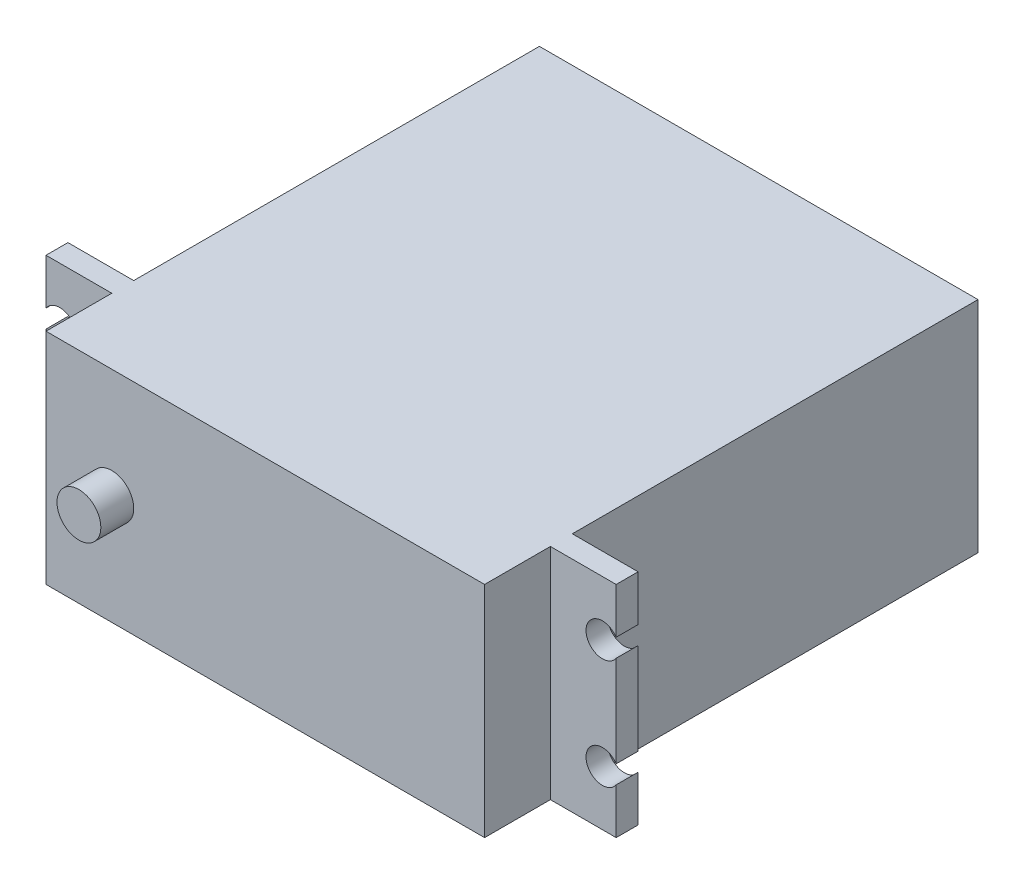
SolidWorks part; units mm, degrees
ref_plane "Plan de face" through (0, 0, 0) normal (0, 0, 1) x (1, 0, 0)
ref_plane "Plan de dessus" through (0, 0, 0) normal (0, 1, 0) x (1, 0, 0)
ref_plane "Plan de droite" through (0, 0, 0) normal (1, 0, 0) x (0, 0, -1)
sketch "Esquisse1" plane through (0, 0, 0) normal (0, 0, 1) x (1, 0, 0)
  line L1 (0, 0) -> (40, 0)
  line L2 (0, 0) -> (0, 20)
  line L3 (0, 20) -> (40, 20)
  line L4 (40, 0) -> (40, 20)
  dimension "D1" = 20
  dimension "D2" = 40
extrude "Boss.-Extru.1" add sketch "Esquisse1" along normal blind 45
sketch "Esquisse2" plane through (0, 0, 45) normal (0, 0, 1) x (1, 0, 0)
  line L0 (40, 20) -> (0, 20) construction
  line L1 (0, 20) -> (0, 0) construction
  circle A0 centre (6, 10) radius 2
  dimension "D1" = 4
  dimension "D2" = 10
  dimension "D3" = 6
extrude "Boss.-Extru.2" add sketch "Esquisse2" along normal blind 3
sketch "Esquisse3" plane through (0, 0, 0) normal (-1, 0, 0) x (0, 0, 1)
  line L0 (45, 20) -> (0, 20) construction
  line L1 (37, 20) -> (39, 20)
  line L2 (37, 20) -> (37, 0)
  line L3 (37, 0) -> (39, 0)
  line L4 (39, 20) -> (39, 0)
  line L5 (45, 0) -> (0, 0) construction
  line L6 (45, 20) -> (45, 0) construction
  dimension "D1" = 2
  dimension "D2" = 6
extrude "Boss.-Extru.3" add sketch "Esquisse3" along normal blind 6
sketch "Esquisse4" plane through (40, 0, 0) normal (1, 0, 0) x (0, 0, -1)
  line L0 (-45, 20) -> (0, 20) construction
  line L1 (-39, 20) -> (-37, 20)
  line L2 (-39, 20) -> (-39, 0)
  line L3 (-39, 0) -> (-37, 0)
  line L4 (-37, 20) -> (-37, 0)
  line L5 (-45, 0) -> (0, 0) construction
  line L6 (-45, 0) -> (-45, 20) construction
  dimension "D1" = 6
  dimension "D2" = 2
extrude "Boss.-Extru.4" add sketch "Esquisse4" along normal blind 6
sketch "Esquisse5" plane through (0, 0, 39) normal (0, 0, 1) x (1, 0, 0)
  line L0 (0, 20) -> (0, 0) construction
  line L1 (0, 0) -> (0, 20) construction
  line L2 (40, 0) -> (40, 20) construction
  line L3 (40, 20) -> (40, 0) construction
  line L4 (46, 20) -> (40, 20) construction
  line L5 (46, 0) -> (40, 0) construction
  line L6 (-6, 20) -> (0, 20) construction
  line L7 (-6, 0) -> (0, 0) construction
  circle A0 centre (-4.75, 15) radius 1.5
  circle A1 centre (44.75, 15) radius 1.5
  circle A2 centre (44.75, 5) radius 1.5
  circle A3 centre (-4.75, 5) radius 1.5
  dimension "D2" = 3
  dimension "D3" = 3
  dimension "D4" = 3
  dimension "D5" = 3
  dimension "D1" = 4.75
  dimension "D6" = 4.75
  dimension "D7" = 4.75
  dimension "D8" = 4.75
  dimension "D9" = 5
  dimension "D10" = 5
  dimension "D11" = 5
  dimension "D12" = 5
extrude "Enlèv. mat.-Extru.1" cut sketch "Esquisse5" against normal blind 6
